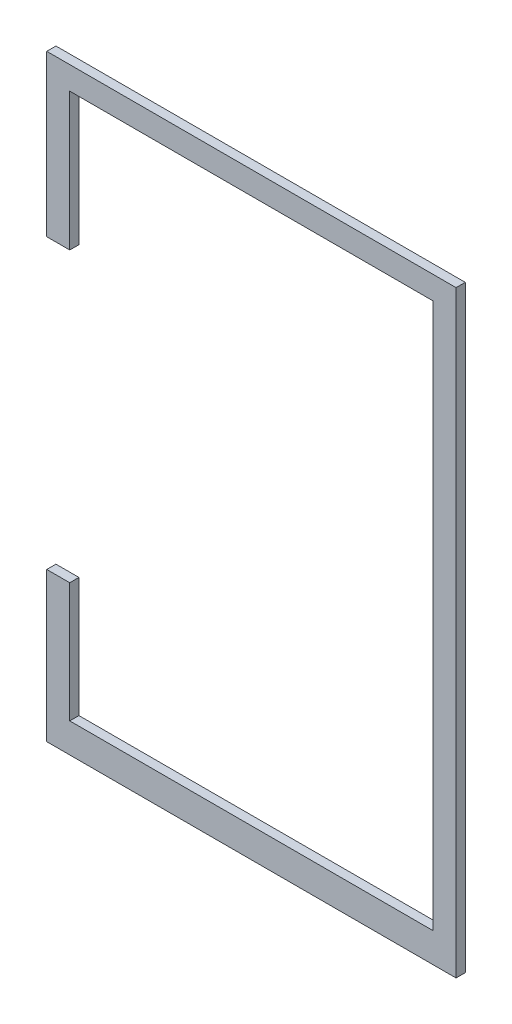
SolidWorks part; units mm, degrees
ref_plane "Front Plane" through (0, 0, 0) normal (1, 0, 0) x (0, 1, 0)
ref_plane "Top Plane" through (0, 0, 0) normal (0, 0, 1) x (0, 1, 0)
ref_plane "Right Plane" through (0, 0, 0) normal (0, 1, 0) x (-1, 0, 0)
sketch "Sketch3" plane through (0, 0, 0) normal (0, 0, 1) x (0, 1, 0)
  line L0 (-124.7446, -70.8775) -> (115.2554, -70.8775) construction
  line L5 (125.2554, 97.1225) -> (55.4224, 97.1225)
  line L6 (125.2554, 97.1225) -> (125.2554, -80.8775)
  line L7 (125.2554, -80.8775) -> (-134.7446, -80.8775)
  line L8 (-134.7446, 97.1225) -> (-134.7446, -80.8775)
  line L9 (115.2554, 87.1225) -> (55.4224, 87.1225)
  line L10 (115.2554, 87.1225) -> (115.2554, -70.8775)
  line L11 (115.2554, -70.8775) -> (-121.9124, -70.8775)
  line L12 (-121.9124, 87.1225) -> (-121.9124, -70.8775)
  line L13 (55.4224, 97.1225) -> (55.4224, 87.1225)
  line L14 (-69.877, 97.1225) -> (-69.877, 87.1225)
  line L15 (-69.877, 97.1225) -> (-134.7446, 97.1225)
  line L16 (-69.877, 87.1225) -> (-121.9124, 87.1225)
extrude "Boss-Extrude1" add sketch "Sketch3" against normal blind 4
